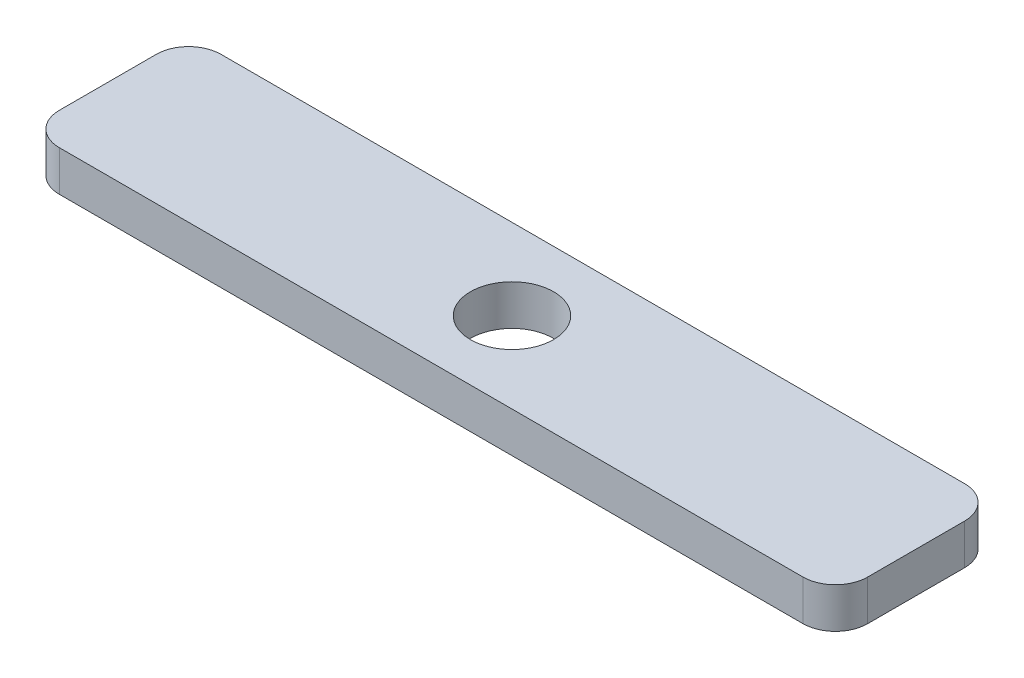
SolidWorks part; units mm, degrees
ref_plane "Front Plane" through (0, 0, 0) normal (0, 0, 1) x (1, 0, 0)
ref_plane "Top Plane" through (0, 0, 0) normal (0, 1, 0) x (1, 0, 0)
ref_plane "Right Plane" through (0, 0, 0) normal (1, 0, 0) x (0, 0, -1)
sketch "Sketch1" plane through (0, 0, 0) normal (0, 1, 0) x (1, 0, 0)
  line L1 (-31.75, -6.35) -> (31.75, -6.35)
  line L2 (-31.75, -6.35) -> (-31.75, 6.35)
  line L3 (-31.75, 6.35) -> (31.75, 6.35)
  line L4 (31.75, -6.35) -> (31.75, 6.35)
  line L5 (-31.75, -6.35) -> (31.75, 6.35) construction
  line L6 (-31.75, 6.35) -> (31.75, -6.35) construction
  circle A0 centre (0, 0) radius 3.2639
  point P0 (0, 0)
  dimension "D3" = 6.5278
  dimension "D1" = 63.5
  dimension "D2" = 12.7
extrude "Boss-Extrude1" add sketch "Sketch1" along normal blind 3.175
fillet "Fillet1" radius 2.54 4 edges at (-31.75, 1.5875, 6.35) (-31.75, 1.5875, -6.35) (31.75, 1.5875, -6.35) (31.75, 1.5875, 6.35)
